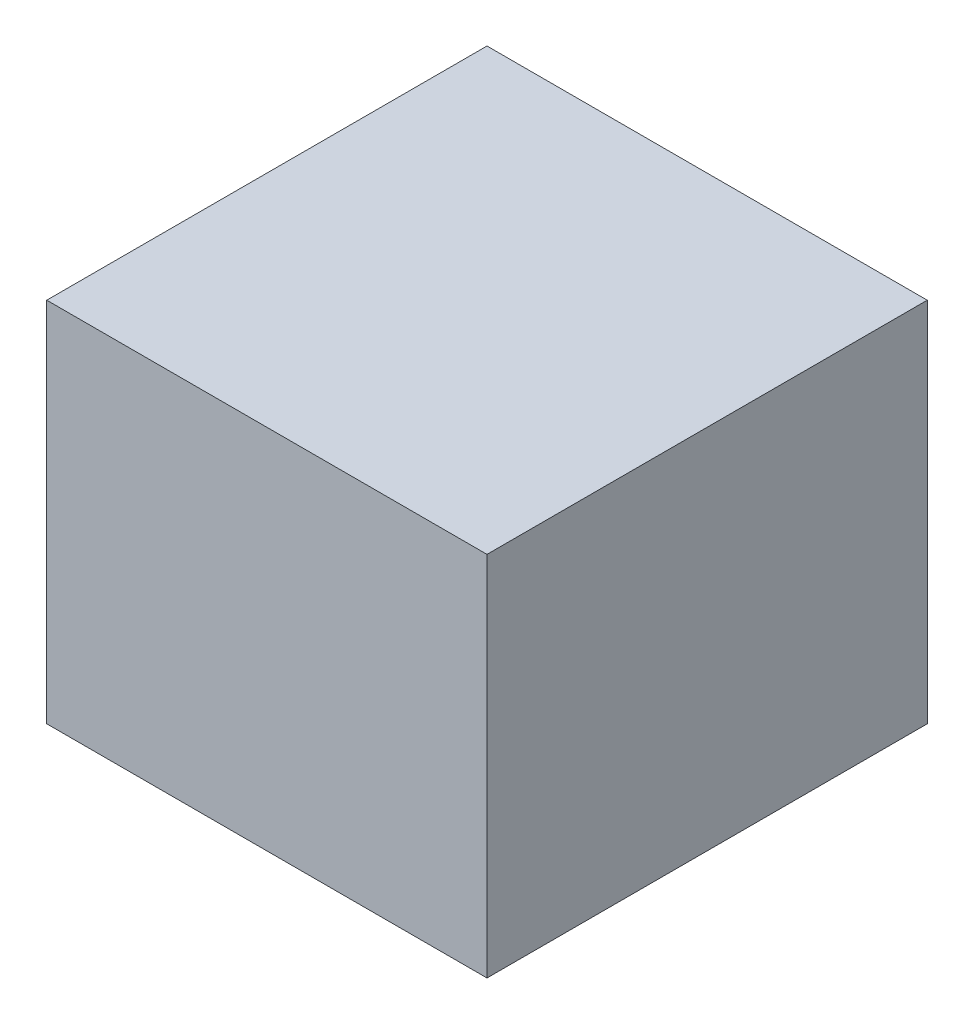
SolidWorks part; units mm, degrees
ref_plane "前视基准面" through (0, 0, 0) normal (0, 0, 1) x (1, 0, 0)
ref_plane "上视基准面" through (0, 0, 0) normal (0, 1, 0) x (1, 0, 0)
ref_plane "右视基准面" through (0, 0, 0) normal (1, 0, 0) x (0, 0, -1)
other "Configuration Table"
sketch "草图1" plane through (0, 0, 0) normal (0, 1, 0) x (1, 0, 0)
  line L1 (0, 0) -> (30, 0)
  line L2 (0, 0) -> (0, -30)
  line L3 (0, -30) -> (30, -30)
  line L4 (30, 0) -> (30, -30)
extrude "凸台-拉伸1" add sketch "草图1" along normal blind 25
